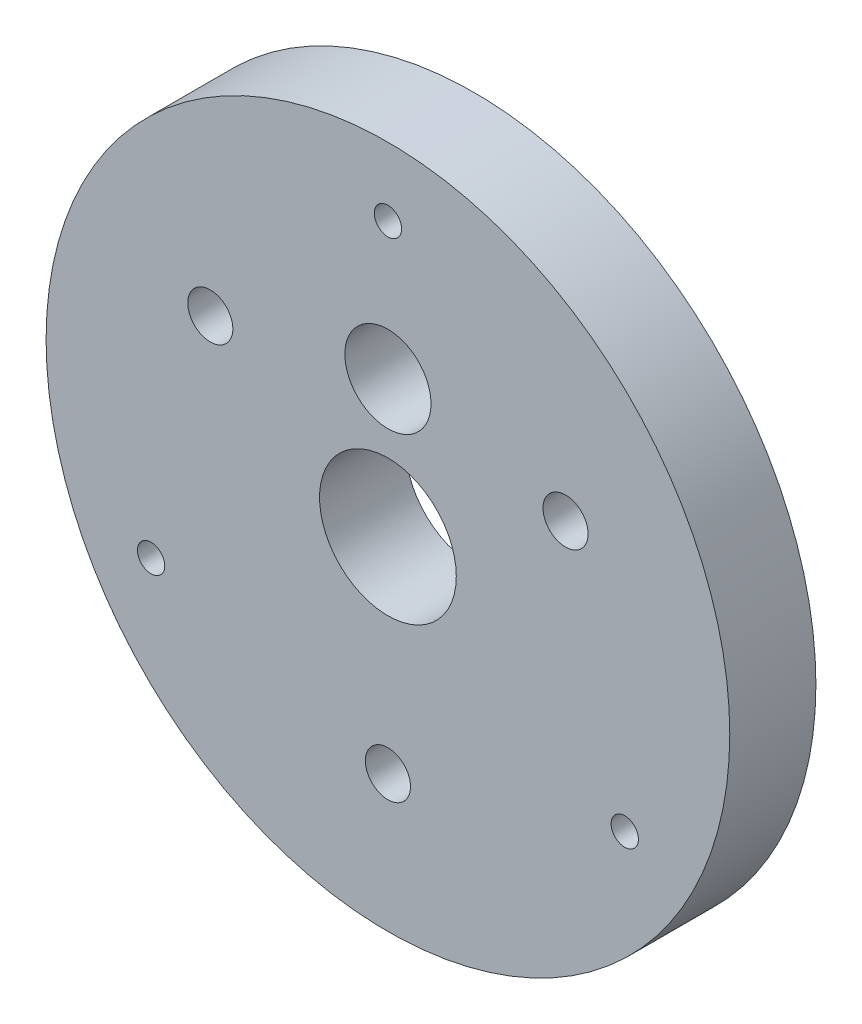
SolidWorks part; units mm, degrees
ref_plane "Front Plane" through (0, 0, 0) normal (0, 0, 1) x (1, 0, 0)
ref_plane "Top Plane" through (0, 0, 0) normal (0, 1, 0) x (1, 0, 0)
ref_plane "Right Plane" through (0, 0, 0) normal (1, 0, 0) x (0, 0, -1)
sketch "Sketch1" plane through (0, 0, 0) normal (0, 0, 1) x (1, 0, 0)
  line L0 (0, 0) -> (0, 20) construction
  line L1 (0, 0) -> (-12.9904, 7.5) construction
  circle A0 centre (0, 0) radius 25
  circle A1 centre (0, 0) radius 5
  circle A2 centre (0, 0) radius 20 construction
  circle A3 centre (0, 20) radius 1
  circle A4 centre (17.3205, -10) radius 1
  circle A5 centre (-17.3205, -10) radius 1
  circle A6 centre (0, 10) radius 3.15
  circle A7 centre (-12.9904, 7.5) radius 1.65
  circle A8 centre (12.9904, 7.5) radius 1.65
  circle A9 centre (0, -15) radius 1.65
  point P14 (0, 0)
  point P16 (29.5375, 7.5)
  point P17 (0, 0)
  point P23 (0, 0)
  dimension "D1" = 50
  dimension "D2" = 10
  dimension "D3" = 40
  dimension "D4" = 2
  dimension "D6" = 6.3
  dimension "D10" = 3.3
  dimension "D7" = 10
  dimension "D8" = 15
  dimension "D9" = 60
  dimension "D5" = 3
  dimension "D11" = 3
extrude "Boss-Extrude1" add sketch "Sketch1" along normal blind 6.3
